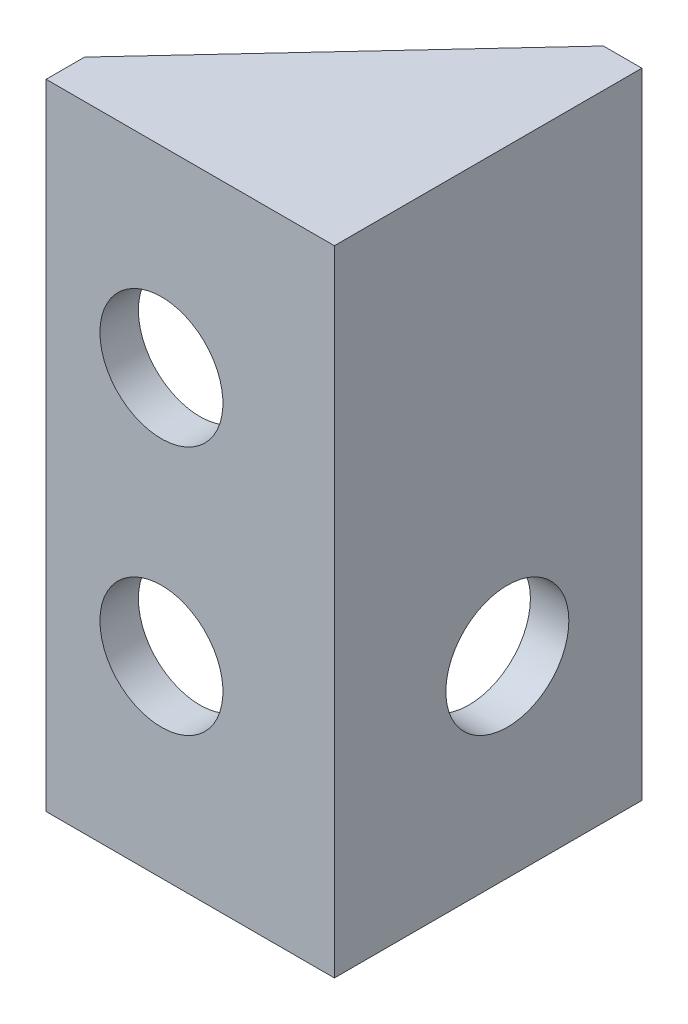
SolidWorks part; units mm, degrees
ref_plane "前视基准面" through (0, 0, 0) normal (0, 0, 1) x (1, 0, 0)
ref_plane "上视基准面" through (0, 0, 0) normal (0, 1, 0) x (1, 0, 0)
ref_plane "右视基准面" through (0, 0, 0) normal (1, 0, 0) x (0, 0, -1)
sketch "草图1" plane through (0, 0, 0) normal (0, 1, 0) x (1, 0, 0)
  line L0 (0, 0) -> (7.5, 0)
  line L1 (7.5, 0) -> (7.5, 8)
  line L2 (7.5, 8) -> (6.5, 8)
  line L3 (6.5, 8) -> (6.5, 1)
  line L4 (6.5, 1) -> (0, 1)
  line L5 (0, 1) -> (0, 0)
  dimension "D1" = 7.5
  dimension "D2" = 1
  dimension "D3" = 1
  dimension "D4" = 8
extrude "凸台-拉伸1" add sketch "草图1" along normal blind 16.5
sketch "草图2" plane through (7.5, 0, 0) normal (1, 0, 0) x (0, 0, -1)
  line L0 (0, 16.5) -> (0, 0) construction
  line L2 (0, 5) -> (7.0901, 5) construction
  line L4 (0, 0) -> (8, 0) construction
  circle A0 centre (4.5, 5) radius 1.6
  dimension "D1" = 3.2
  dimension "D2" = 5
  dimension "D3" = 4.5
extrude "切除-拉伸1" cut sketch "草图2" against normal blind 6
sketch "草图3" plane through (0, 0, -1) normal (0, 0, -1) x (-1, 0, 0)
  line L0 (-6.5, 16.5) -> (-6.5, 0) construction
  line L2 (-7.5, 8.25) -> (4.8779, 8.25) construction
  line L3 (-7.5, 16.5) -> (-7.5, 0) construction
  circle A0 centre (-3, 5) radius 1.6
  circle A1 centre (-3, 11.5) radius 1.6
  dimension "D2" = 3.2
  dimension "D1" = 3.5
  dimension "D4" = 6.5
extrude "切除-拉伸2" cut sketch "草图3" against normal blind 10
sketch "草图4" plane through (0, 0, 0) normal (0, -1, 0) x (1, 0, 0)
  line L0 (0, -1) -> (6.5, -1)
  line L1 (6.5, -1) -> (6.5, -8)
  line L2 (6.5, -8) -> (0, -1)
extrude "凸台-拉伸2" add sketch "草图4" against normal blind 1
sketch "草图5" plane through (0, 16.5, 0) normal (0, 1, 0) x (1, 0, 0)
  line L0 (0, 1) -> (6.5, 1)
  line L1 (6.5, 1) -> (6.5, 8)
  line L2 (6.5, 8) -> (0, 1)
extrude "凸台-拉伸3" add sketch "草图5" against normal blind 1
